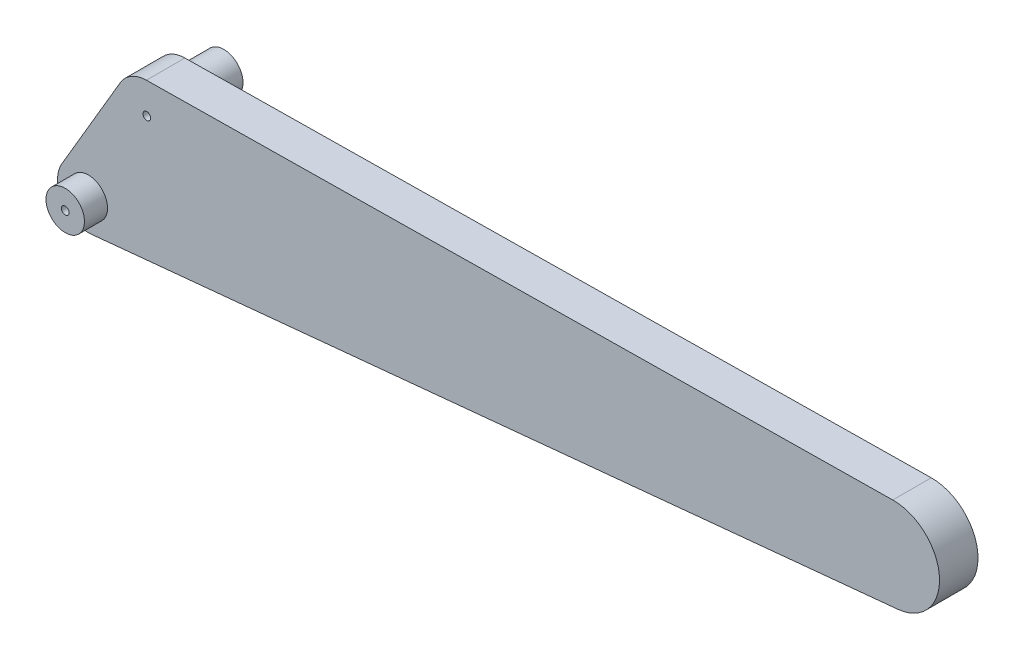
SolidWorks part; units mm, degrees
ref_plane "Front Plane" through (0, 0, 0) normal (0, 0, 1) x (1, 0, 0)
ref_plane "Top Plane" through (0, 0, 0) normal (0, 1, 0) x (1, 0, 0)
ref_plane "Right Plane" through (0, 0, 0) normal (1, 0, 0) x (0, 0, -1)
sketch "Sketch2" plane through (0, 0, 0) normal (0, 0, 1) x (1, 0, 0)
  line L0 (-7.5998, -12.9323) -> (0, 0)
  line L1 (0, 0) -> (97, -0.7468)
  dimension "D1" = 97
  dimension "D2" = 15
  dimension "D3" = 120
sketch "Sketch3" plane through (0, 0, 0) normal (0, 0, 1) x (1, 0, 0)
  line L0 (-11.0484, -10.9056) -> (-3.4486, 2.0266)
  line L1 (-0.0517, 3.9997) -> (96.9225, 5.2527)
  line L2 (97.581, -6.7186) -> (-7.2125, -16.9135)
  circle A0 centre (-7.5998, -12.9323) radius 2.5
  arc A1 (-11.0484, -10.9056) -> (-7.2125, -16.9135) centre (-7.5998, -12.9323) ccw
  circle A2 centre (0, 0) radius 2.5
  arc A3 (-0.0517, 3.9997) -> (-3.4486, 2.0266) centre (0, 0) ccw
  arc A4 (97.581, -6.7186) -> (96.9225, 5.2527) centre (97, -0.7468) ccw
  dimension "D1" = 5
  dimension "D2" = 8
  dimension "D3" = 5
  dimension "D4" = 8
  dimension "D5" = 12
extrude "Boss-Extrude1" add sketch "Sketch3" along normal blind 5
sketch "Sketch4" plane through (0, 0, 5) normal (0, 0, 1) x (1, 0, 0)
  circle A0 centre (0, 0) radius 2.5
  circle A1 centre (0, 0) radius 0.5
  dimension "D1" = 1
  dimension "D2" = 5
extrude "Boss-Extrude2" add sketch "Sketch4" against normal blind 10
sketch "Sketch5" plane through (0, 0, 0) normal (0, 0, -1) x (-1, 0, 0)
  circle A0 centre (7.5998, -12.9323) radius 2.5
  circle A1 centre (7.5998, -12.9323) radius 0.5
  dimension "D1" = 1
  dimension "D2" = 5
extrude "Boss-Extrude3" add sketch "Sketch5" against normal blind 8
